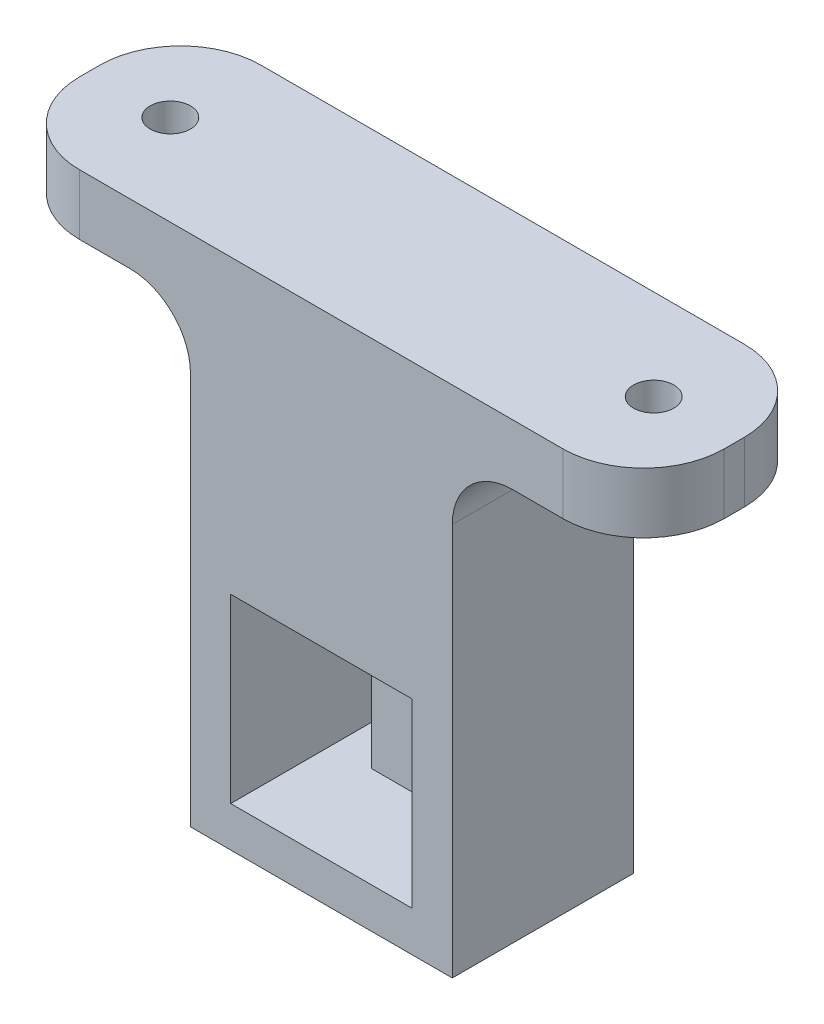
SolidWorks part; units mm, degrees
ref_plane "Front Plane" through (0, 0, 0) normal (0, 0, 1) x (1, 0, 0)
ref_plane "Top Plane" through (0, 0, 0) normal (0, 1, 0) x (1, 0, 0)
ref_plane "Right Plane" through (0, 0, 0) normal (1, 0, 0) x (0, 0, -1)
sketch "Sketch1" plane through (0, 0, -28) normal (0, 0, -1) x (-1, 0, 0)
  line L4 (-2.5, 10.5) -> (-2.5, 1.5)
  line L5 (-2.5, 1.5) -> (2.5, 1.5)
  line L6 (2.5, 1.5) -> (2.5, 10.5)
  line L7 (2.5, 10.5) -> (-2.5, 10.5)
  line L8 (-2.5, 10.5) -> (-2.5, 1.5)
  line L9 (-2.5, 1.5) -> (2.5, 1.5)
  line L10 (2.5, 1.5) -> (2.5, 10.5)
  line L11 (2.5, 10.5) -> (-2.5, 10.5)
  line L12 (4.5, 1.5) -> (4.5, 10.5)
  line L13 (-4.5, 1.5) -> (4.5, 1.5)
  line L14 (-4.5, 10.5) -> (-4.5, 1.5)
  line L15 (4.5, 10.5) -> (-4.5, 10.5)
  line L16 (4.5, 1.5) -> (4.5, 10.5)
  line L17 (-4.5, 1.5) -> (4.5, 1.5)
  line L18 (-4.5, 10.5) -> (-4.5, 1.5)
  line L19 (4.5, 10.5) -> (-4.5, 10.5)
  line L24 (6.5, -0.5) -> (6.5, 12.5)
  line L25 (-6.5, -0.5) -> (6.5, -0.5)
  line L26 (-6.5, 12.5) -> (-6.5, -0.5)
  line L27 (6.5, 12.5) -> (-6.5, 12.5)
  line L28 (6.5, -0.5) -> (6.5, 12.5)
  line L29 (-6.5, -0.5) -> (6.5, -0.5)
  line L30 (-6.5, 12.5) -> (-6.5, -0.5)
  line L31 (6.5, 12.5) -> (-6.5, 12.5)
  line M13 (-2.5, 10.5) -> (-2.5, 1.5)
  line M14 (-2.5, 1.5) -> (2.5, 1.5)
  line M15 (2.5, 1.5) -> (2.5, 10.5)
  line M16 (2.5, 10.5) -> (-2.5, 10.5)
  dimension "D1" = 0
  dimension "D2" = 0
  dimension "D3" = 2
extrude "Boss-Extrude1" add sketch "Sketch1" along normal blind 4 contours M16 M13 M14 M15 | L28 L31 L30 L29 L19 L16 L17 L18 M14 M16
sketch "Sketch2" plane through (0, 0, -28) normal (0, 0, 1) x (1, 0, 0)
  line L0 (-4.5, 10.5) -> (-4.5, 1.5)
  line L1 (-4.5, 1.5) -> (4.5, 1.5)
  line L2 (4.5, 1.5) -> (4.5, 10.5)
  line L3 (4.5, 10.5) -> (-4.5, 10.5)
  line L4 (-6.5, 12.5) -> (-6.5, -0.5)
  line L5 (-6.5, -0.5) -> (6.5, -0.5)
  line L6 (6.5, -0.5) -> (6.5, 12.5)
  line L7 (6.5, 12.5) -> (-6.5, 12.5)
  line L8 (-6.5, 12.5) -> (-6.5, -0.5)
  line L9 (-6.5, -0.5) -> (6.5, -0.5)
  line L10 (6.5, -0.5) -> (6.5, 12.5)
  line L11 (6.5, 12.5) -> (-6.5, 12.5)
  dimension "D1" = 0
  dimension "D2" = 2
extrude "Boss-Extrude2" add sketch "Sketch2" along normal blind 5
sketch "Sketch3" plane through (0, 12.5, 0) normal (0, 1, 0) x (1, 0, 0)
  line L4 (-6.5, 32) -> (-6.5, 23)
  line L5 (-6.5, 23) -> (6.5, 23)
  line L6 (6.5, 23) -> (6.5, 32)
  line L7 (6.5, 32) -> (-6.5, 32)
  line L8 (-6.5, 32) -> (-6.5, 23)
  line L9 (-6.5, 23) -> (6.5, 23)
  line L10 (6.5, 23) -> (6.5, 32)
  line L11 (6.5, 32) -> (-6.5, 32)
  dimension "D1" = 0
extrude "Boss-Extrude3" add sketch "Sketch3" along normal up to surface (12.5 mm away)
sketch "Sketch4" plane through (0, 25, 0) normal (0, 1, 0) x (1, 0, 0)
  line L0 (-16, 28) -> (-16, -24) construction
  line L1 (-12, 23) -> (12, 23)
  line L2 (-16, 27) -> (-16, 28)
  line L3 (-12, 32) -> (12, 32)
  line L4 (16, 27) -> (16, 28)
  line L5 (16, -24) -> (16, 28) construction
  line L6 (6.5, 23) -> (-6.5, 23) construction
  line L7 (12, 32) -> (-12, 32) construction
  arc A0 (12, 32) -> (16, 28) centre (12, 28) cw
  arc A1 (12, 23) -> (16, 27) centre (12, 27) ccw
  arc A2 (-12, 23) -> (-16, 27) centre (-12, 27) cw
  arc A3 (-16, 28) -> (-12, 32) centre (-12, 28) cw
  point P6 (16, 20.6842)
  point P17 (16, 23)
  point P20 (-16, 23)
  dimension "D1" = 4
extrude "Boss-Extrude4" add sketch "Sketch4" against normal blind 3
fillet "Fillet1" radius 3 2 edges at (6.5, 22, -27.5) (-6.5, 22, -27.5)
sketch "Sketch5" plane through (0, 22, 0) normal (0, -1, 0) x (1, 0, 0)
  line L0 (-16, -28) -> (-16, -27) construction
  line L1 (16, -27) -> (16, -28) construction
  circle A0 centre (-12, -27.5) radius 1
  circle A1 centre (12, -27.5) radius 1
  point P6 (-16, -27.5)
  point P7 (-12.5838, -27.5)
  point P9 (0, 0)
  point P10 (0, 0)
  point P14 (16, -27.5)
  dimension "D1" = 2
extrude "Cut-Extrude1" cut sketch "Sketch5" against normal through all
